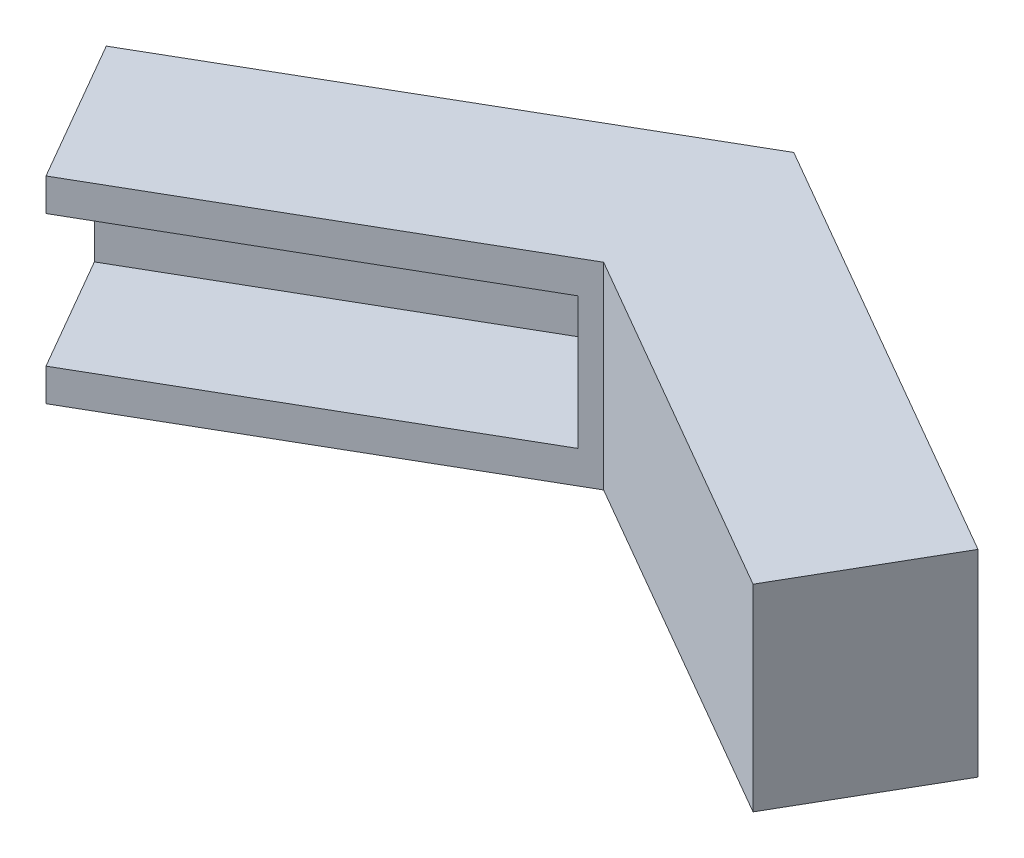
SolidWorks part; units mm, degrees
ref_plane "Front Plane" through (0, 0, 0) normal (0, 0, 1) x (1, 0, 0)
ref_plane "Top Plane" through (0, 0, 0) normal (0, 1, 0) x (1, 0, 0)
ref_plane "Right Plane" through (0, 0, 0) normal (1, 0, 0) x (0, 0, -1)
sketch "Sketch6" plane through (0, 0, 0) normal (0, 1, 0) x (1, 0, 0)
  line L0 (0, 0) -> (-51.9615, -30) construction
  line L1 (0, 0) -> (51.9615, -30) construction
  line L2 (0, 0) -> (0, -30) construction
  line L3 (-51.9615, -30) -> (51.9615, -30) construction
  line L4 (-51.9615, -30) -> (-54.3131, -25.9269) construction
  line L5 (51.9615, -30) -> (54.3131, -25.9269) construction
  line L6 (0, 0) -> (0, 5.4308) construction
  line L7 (-54.3131, -25.9269) -> (0, 5.4308) construction
  line L8 (0, 5.4308) -> (54.3131, -25.9269) construction
  line L9 (-54.3131, -25.9269) -> (-64.4631, -8.3466) construction
  line L10 (54.3131, -25.9269) -> (64.4631, -8.3466) construction
  line L11 (0, 0) -> (-2.1651, -1.25) construction
  line L12 (0, 5.4308) -> (0, 28.8712) construction
  line L13 (-64.4631, -8.3466) -> (0, 28.8712) construction
  line L14 (0, 28.8712) -> (64.4631, -8.3466) construction
  line L15 (-64.4631, -8.3466) -> (-66.9631, -4.0165) construction
  line L16 (64.4631, -8.3466) -> (66.9631, -4.0165) construction
  line L17 (0, 28.8712) -> (0, 34.6447) construction
  line L18 (-66.9631, -4.0165) -> (0, 34.6447) construction
  line L19 (66.9631, -4.0165) -> (0, 34.6447) construction
  line L20 (0, 5.4308) -> (2.5, 5.4308) construction
  line L21 (0, 5.4308) -> (-2.5, 5.4308) construction
  line L22 (0, 5.4308) -> (-2.5, 3.9874) construction
  line L23 (0, 5.4308) -> (2.5, 3.9874) construction
  line L24 (2.5, 5.4308) -> (2.5, 3.9874) construction
  line L25 (-2.5, 5.4308) -> (-2.5, 3.9874) construction
  arc A0 (-16.4811, -9.5153) -> (0, -19.0307) centre (0, 0) ccw construction
sketch "Sketch7" plane through (0, 0, 0) normal (0, 1, 0) x (1, 0, 0)
  line L0 (-66.9631, -4.0165) -> (-54.3131, -25.9269)
  line L2 (54.3131, -25.9269) -> (66.9631, -4.0165)
  line L3 (66.9631, -4.0165) -> (0, 34.6447)
  line L4 (0, 34.6447) -> (-66.9631, -4.0165)
  line L8 (-54.3131, -25.9269) -> (0, 5.4308)
  line L9 (0, 5.4308) -> (54.3131, -25.9269)
extrude "Boss-Extrude3" add sketch "Sketch7" along normal blind 30.3
sketch "Sketch8" plane through (-2.3516, 0, -4.0731) normal (0.5, 0, 0.866) x (0.866, 0, -0.5)
  line L0 (-0.1714, 0) -> (-0.1714, 30.3) construction
  line L1 (-60, 30.3) -> (2.7154, 30.3) construction
  line L2 (-0.1714, 0) -> (-0.1714, 5) construction
  line L3 (-0.1714, 5) -> (-60, 5)
  line L4 (-60, 30.3) -> (-60, 0) construction
  line L5 (-0.1714, 30.3) -> (-0.1714, 25.3) construction
  line L6 (-0.1714, 25.3) -> (-60, 25.3)
  line L7 (-60, 25.3) -> (-60, 5)
  line L8 (-0.1714, 25.3) -> (-0.1714, 5)
extrude "Cut-Extrude5" cut sketch "Sketch8" against normal blind 20.3
